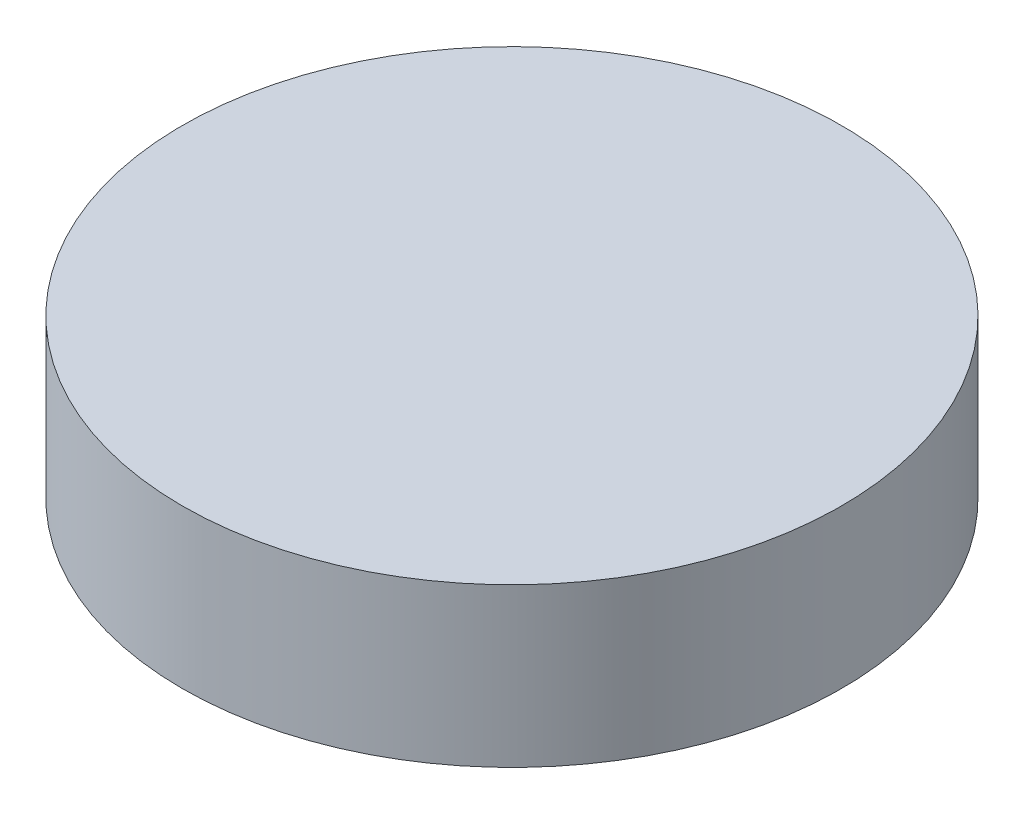
SolidWorks part; units mm, degrees
ref_plane "Front Plane" through (0, 0, 0) normal (0, 0, 1) x (1, 0, 0)
ref_plane "Top Plane" through (0, 0, 0) normal (0, 1, 0) x (1, 0, 0)
ref_plane "Right Plane" through (0, 0, 0) normal (1, 0, 0) x (0, 0, -1)
other "Configuration Table"
sketch "Sketch1" plane through (0, 0, 0) normal (0, 1, 0) x (1, 0, 0)
  circle A0 centre (650, 50) radius 25
extrude "PACK_ayar_ayagi_2" add sketch "Sketch1" along normal blind 12 separate body
